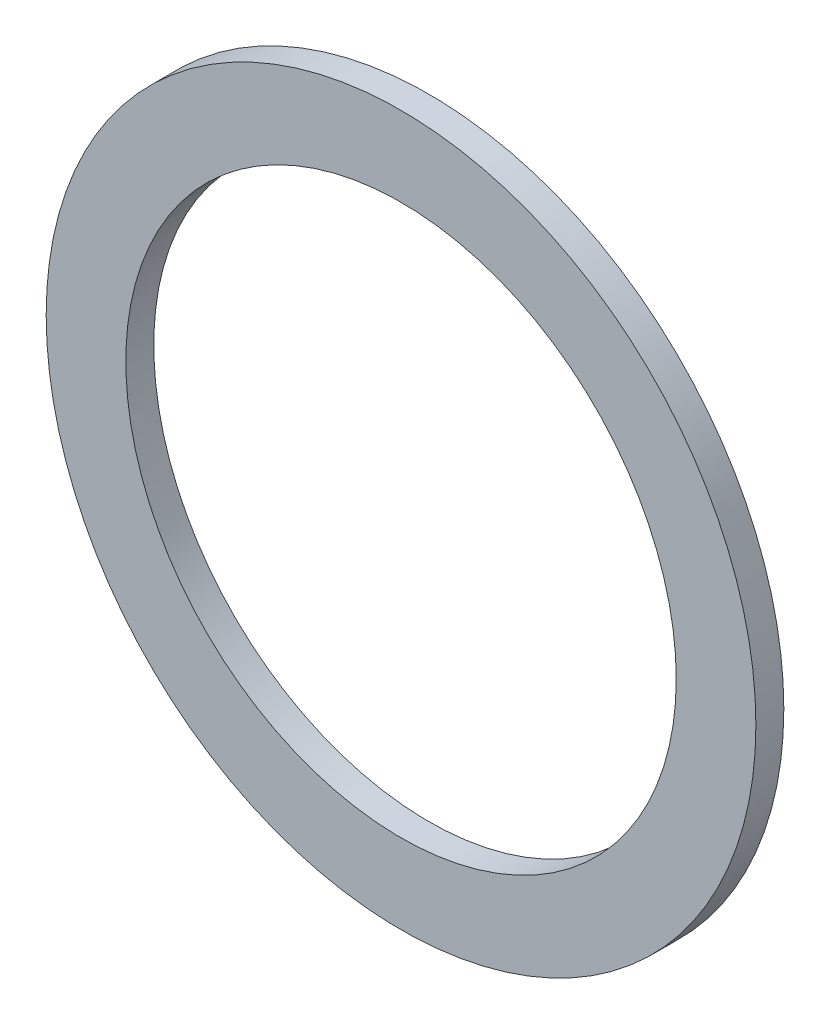
SolidWorks part; units mm, degrees
ref_plane "Front Plane" through (0, 0, 0) normal (0, 0, 1) x (1, 0, 0)
ref_plane "Top Plane" through (0, 0, 0) normal (0, 1, 0) x (1, 0, 0)
ref_plane "Right Plane" through (0, 0, 0) normal (1, 0, 0) x (0, 0, -1)
sketch "Sketch1" plane through (0, 0, 0) normal (0, 0, 1) x (1, 0, 0)
  circle A0 centre (0, 0) radius 49.25
  circle A1 centre (0, 0) radius 63.5
  dimension "D1" = 98.5
  dimension "D2" = 127
extrude "Boss-Extrude1" add sketch "Sketch1" along normal blind 5
